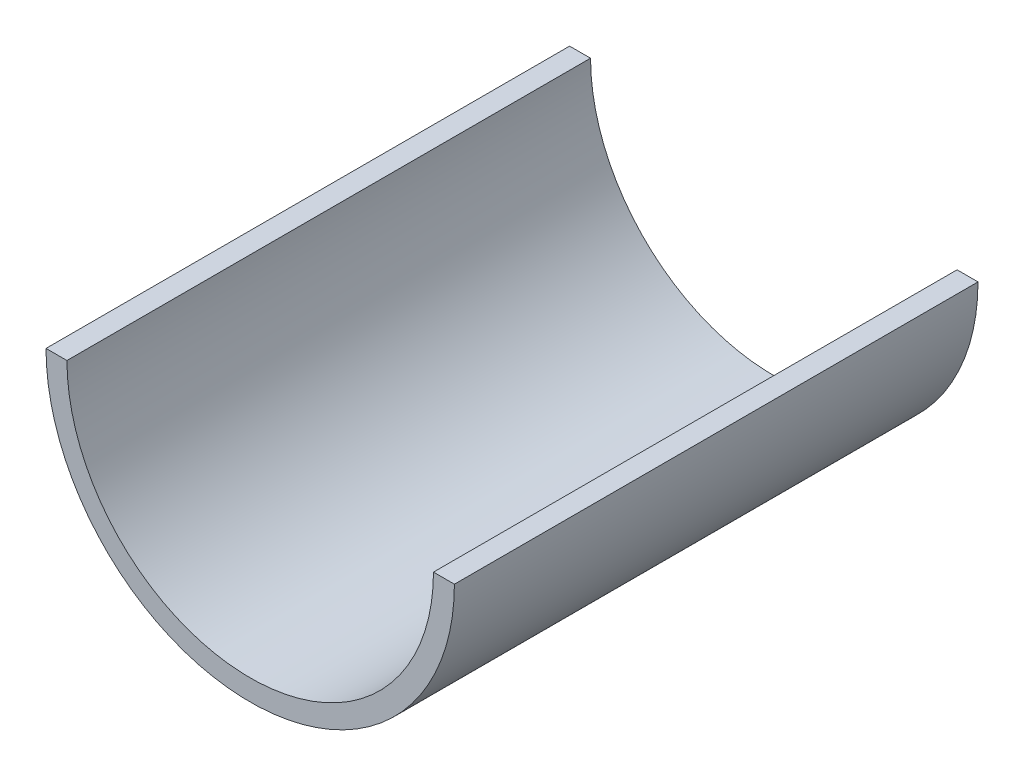
SolidWorks part; units mm, degrees
ref_plane "Front Plane" through (0, 0, 0) normal (0, 0, 1) x (1, 0, 0)
ref_plane "Top Plane" through (0, 0, 0) normal (0, 1, 0) x (1, 0, 0)
ref_plane "Right Plane" through (0, 0, 0) normal (1, 0, 0) x (0, 0, -1)
sketch "Sketch1" plane through (0, 0, 0) normal (0, 0, 1) x (1, 0, 0)
  line L0 (38.5, 0) -> (-38.5, 0) construction
  arc A0 (-35, 0) -> (35, 0) centre (0, 0) ccw
  dimension "D1" = 35
extrude "Extrude-Thin1" add sketch "Sketch1" along normal blind 100 thin
